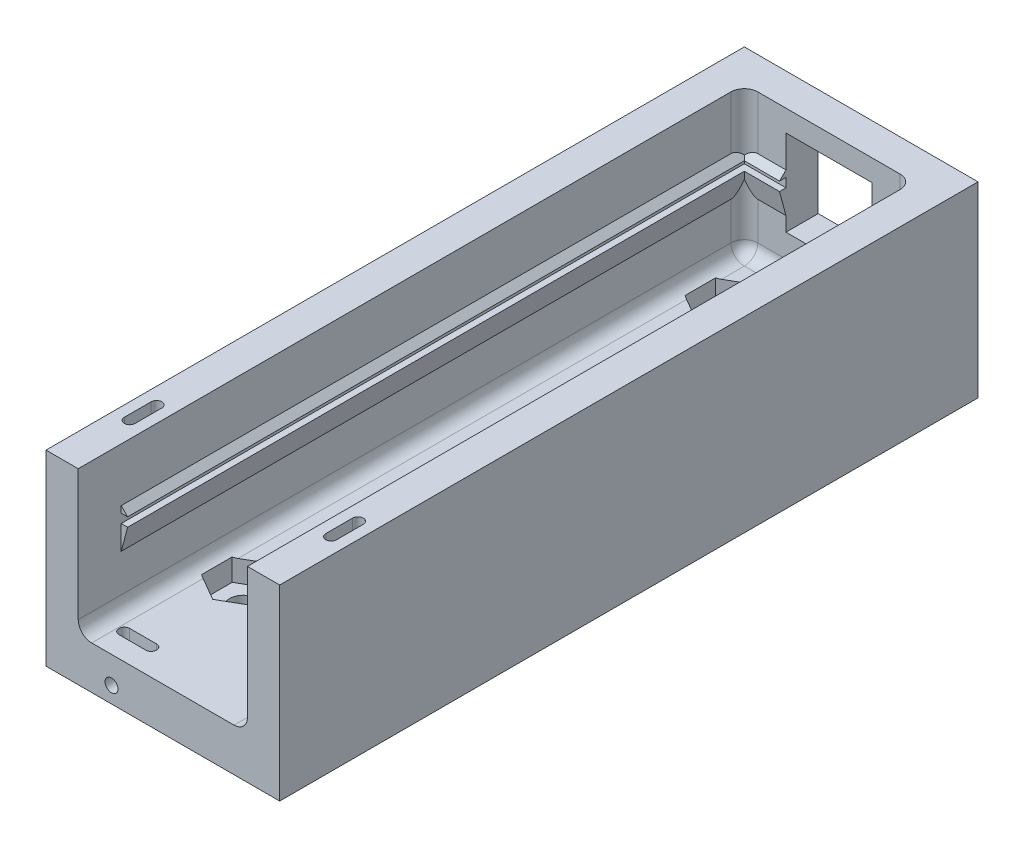
SolidWorks part; units mm, degrees
ref_plane "Front Plane" through (0, 0, 0) normal (0, 0, 1) x (1, 0, 0)
ref_plane "Top Plane" through (0, 0, 0) normal (0, 1, 0) x (1, 0, 0)
ref_plane "Right Plane" through (0, 0, 0) normal (1, 0, 0) x (0, 0, -1)
sketch "Sketch1" plane through (0, 0, 0) normal (0, 0, 1) x (1, 0, 0)
  line L0 (0, 8.7277) -> (0, -3.7047) construction
  line L2 (10.0012, 12.065) -> (10.0012, -8.255)
  line L3 (10.0012, -8.255) -> (-10.0012, -8.255)
  line L4 (-10.0012, 12.065) -> (-10.0012, -8.255)
  line L7 (13.8113, 12.065) -> (10.0012, 12.065)
  line L8 (13.8113, 12.065) -> (13.8113, -13.335)
  line L9 (13.8113, -13.335) -> (-13.8112, -13.335)
  line L10 (-13.8112, 12.065) -> (-13.8112, -13.335)
  line L14 (-10.0012, 12.065) -> (-13.8112, 12.065)
  dimension "D1" = 20.0025
  dimension "D2" = 20.32
  dimension "D3" = 3.81
  dimension "D4" = 3.81
  dimension "D5" = 5.08
  dimension "D6" = 8.255
extrude "Boss-Extrude1" add sketch "Sketch1" along normal blind 82.55
sketch "Sketch3" plane through (0, 0, 82.55) normal (0, 0, 1) x (1, 0, 0)
  line L0 (10.0012, 12.065) -> (10.0012, -8.255) construction
  line L1 (10.0012, 1.7018) -> (9.2392, 1.7018)
  line L2 (10.0012, -8.255) -> (-10.0012, -8.255) construction
  line L3 (10.0012, 0.635) -> (9.2392, 0.635)
  line L4 (-10.0012, 2.4638) -> (-10.0012, 1.7018)
  line L5 (9.2392, 0.635) -> (10.0012, -2.2088)
  line L6 (10.0012, -2.2088) -> (10.0012, 0.635)
  line L7 (9.2392, 1.7018) -> (10.0012, 2.4638)
  line L8 (10.0012, 2.4638) -> (10.0012, 1.7018)
  line L9 (0, 5.2449) -> (0, -5.0535) construction
  line L10 (-9.2392, 1.7018) -> (-10.0012, 2.4638)
  line L11 (-10.0012, -2.2088) -> (-10.0012, 0.635)
  line L12 (-9.2392, 0.635) -> (-10.0012, -2.2088)
  line L13 (-10.0012, 0.635) -> (-9.2392, 0.635)
  line L14 (-10.0012, 1.7018) -> (-9.2392, 1.7018)
  dimension "D1" = 1.0668
  dimension "D2" = 0.762
  dimension "D3" = 0.762
  dimension "D4" = 45
  dimension "D5" = 75
  dimension "D6" = 8.89
extrude "Boss-Extrude2" add sketch "Sketch3" against normal up to surface (77.47 mm away) from offset 5.08 up to face at (0, 0.635, 0) offset against normal yes
sketch "Sketch8" plane through (0, 12.065, 0) normal (0, 1, 0) x (1, 0, 0)
  line L0 (13.8113, -82.55) -> (13.8113, 0) construction
  line L1 (-13.8112, 0) -> (13.8113, 0)
  line L2 (-13.8112, 0) -> (-13.8112, -3.81)
  line L3 (-13.8112, -3.81) -> (13.8113, -3.81)
  line L4 (13.8113, 0) -> (13.8113, -3.81)
  dimension "D1" = 3.81
extrude "Boss-Extrude4" add sketch "Sketch8" against normal up to surface (20.32 mm away) up to face at (0, -8.255, 41.275)
sketch "Sketch9" plane through (-10.0012, 0, 0) normal (1, 0, 0) x (0, 0, -1)
  line L6 (-3.81, 2.4638) -> (-3.81, 1.7018)
  line L7 (-3.81, 1.7018) -> (-4.572, 1.7018)
  line L8 (-3.81, 1.7018) -> (-77.47, 1.7018) construction
  line L9 (-4.572, 1.7018) -> (-3.81, 2.4638)
  line L10 (-3.81, 0.635) -> (-3.81, -2.2088)
  line L11 (-3.81, -2.2088) -> (-4.572, 0.635)
  line L12 (-3.81, 0.635) -> (-77.47, 0.635) construction
  line L13 (-4.572, 0.635) -> (-3.81, 0.635)
  dimension "D4" = 45
  dimension "D5" = 15
extrude "Boss-Extrude5" add sketch "Sketch9" along normal up to surface (20.0025 mm away) up to face at (10.0012, 1.067, 41.4867)
sketch "Sketch10" plane through (0, 0, 0) normal (0, 0, -1) x (-1, 0, 0)
  line L0 (0, 3.2514) -> (0, -1.5042) construction
  line L1 (5.08, -3.9116) -> (-5.08, -3.9116)
  line L2 (5.08, -3.9116) -> (5.08, 6.2484)
  line L3 (5.08, 6.2484) -> (-5.08, 6.2484)
  line L4 (-5.08, -3.9116) -> (-5.08, 6.2484)
  line L7 (2.0868, 1.1684) -> (-3.2166, 1.1684) construction
  line L10 (-9.2392, 1.7018) -> (9.2392, 1.7018) construction
  dimension "D1" = 10.16
  dimension "D2" = 10.16
  dimension "D3" = 0.5334
extrude "Cut-Extrude1" cut sketch "Sketch10" against normal up to next
sketch "Sketch11" plane through (0, 0, 82.55) normal (0, 0, 1) x (1, 0, 0)
  line L0 (13.8113, -13.335) -> (13.8113, 12.065) construction
  line L1 (-13.8112, 12.065) -> (13.8113, 12.065)
  line L2 (-13.8112, 12.065) -> (-13.8112, 8.7884)
  line L3 (-13.8112, 8.7884) -> (13.8113, 8.7884)
  line L4 (13.8113, 12.065) -> (13.8113, 8.7884)
  line L5 (-5.08, 6.2484) -> (5.08, 6.2484) construction
  dimension "D1" = 2.54
extrude "Cut-Extrude2" cut sketch "Sketch11" against normal through all
fillet "Fillet3" radius 1.5875 7 edges at (-10.0012, 5.6261, 3.81) (10.0012, 5.6261, 3.81) (10.0012, -5.2319, 3.81) (-10.0012, -5.2319, 3.81) (10.0012, -8.255, 43.18) (0, -8.255, 3.81) (-10.0012, -8.255, 43.18)
sketch "Sketch13" plane through (0, -8.255, 0) normal (0, 1, 0) x (1, 0, 0)
  line L0 (-7.6519, -79.4512) -> (-4.4769, -79.4512) construction
  line L1 (-7.6519, -78.8162) -> (-4.4769, -78.8162)
  line L2 (-7.6519, -80.0862) -> (-4.4769, -80.0862)
  line L3 (-8.4137, -3.81) -> (8.4137, -3.81) construction
  arc A0 (-7.6519, -78.8162) -> (-7.6519, -80.0862) centre (-7.6519, -79.4512) ccw
  arc A1 (-4.4769, -80.0862) -> (-4.4769, -78.8162) centre (-4.4769, -79.4512) ccw
  point P2 (-6.0644, -79.4512)
  dimension "D3" = 0.635
  dimension "D1" = 75.0062
  dimension "D2" = 3.175
extrude "Cut-Extrude3" cut sketch "Sketch13" against normal blind 2.286
sketch "Sketch14" plane through (0, 8.7884, 0) normal (0, 1, 0) x (1, 0, 0)
  line L0 (-11.9062, -71.387) -> (-11.9062, -74.562) construction
  line L1 (-11.2712, -71.387) -> (-11.2712, -74.562)
  line L2 (-12.5412, -71.387) -> (-12.5412, -74.562)
  line L3 (-10.0012, -5.3975) -> (-10.0012, -82.55) construction
  line L4 (-13.8112, 0) -> (-13.8112, -82.55) construction
  line L5 (-4.4769, -78.8162) -> (-7.6519, -78.8162) construction
  line L6 (0, -43.2809) -> (0, -94.1632) construction
  line L7 (11.9062, -71.387) -> (11.9062, -74.562) construction
  line L8 (11.2712, -71.387) -> (11.2712, -74.562)
  line L9 (12.5412, -71.387) -> (12.5412, -74.562)
  arc A0 (-11.2712, -71.387) -> (-12.5412, -71.387) centre (-11.9062, -71.387) ccw
  arc A1 (-12.5412, -74.562) -> (-11.2712, -74.562) centre (-11.9062, -74.562) ccw
  arc A2 (11.2712, -71.387) -> (12.5412, -71.387) centre (11.9062, -71.387) cw
  arc A3 (12.5412, -74.562) -> (11.2712, -74.562) centre (11.9062, -74.562) cw
  point P2 (-11.9062, -72.9745)
  point P18 (11.9062, -72.9745)
  dimension "D1" = 0.635
  dimension "D2" = 4.2542
  dimension "D3" = 3.175
extrude "Cut-Extrude4" cut sketch "Sketch14" against normal blind 3.175
hole_wizard "#4 Clearance Hole1" positions "Sketch16" profile "Sketch15" hole size "#4" standard "ANSI Inch" end condition up to next
sketch "Sketch16" plane through (0, -8.255, 0) normal (0, 1, 0) x (1, 0, 0)
  line L0 (0, -7.3362) -> (0, -55.1556) construction
  line L2 (8.4137, -82.55) -> (-8.4137, -82.55) construction
  point P0 (-5.715, -10.16)
  point P2 (5.715, -67.31)
  point P4 (-5.715, -67.31)
  point P6 (5.715, -10.16)
  dimension "D1" = 57.15
  dimension "D2" = 11.43
  dimension "D3" = 15.24
sketch "Sketch15" plane through (-5.715, -8.255, 10.16) normal (1, 0, 0) x (0, 0, 1)
  line L0 (0, 0) -> (0, 5.08)
  line L1 (0, 5.08) -> (1.6319, 5.08)
  line L2 (1.6319, 5.08) -> (1.6319, 0)
  line L5 (1.6319, 0) -> (0, 0)
  line L11 (0, -6.35) -> (0, 107.95) construction
  dimension "Thru Hole Dia." = 3.2639
  dimension "Thru Hole Depth" = 5.08
sketch "Sketch17" plane through (0, -8.255, 0) normal (0, 1, 0) x (1, 0, 0)
  line L1 (-5.715, -13.7822) -> (-2.5781, -11.9711)
  line L2 (-2.5781, -11.9711) -> (-2.5781, -8.3489)
  line L3 (-2.5781, -8.3489) -> (-5.715, -6.5378)
  line L4 (-5.715, -6.5378) -> (-8.8519, -8.3489)
  line L5 (-8.8519, -8.3489) -> (-8.8519, -11.9711)
  line L6 (-8.8519, -11.9711) -> (-5.715, -13.7822)
  line L7 (5.715, -13.7822) -> (8.8519, -11.9711)
  line L8 (8.8519, -11.9711) -> (8.8519, -8.3489)
  line L9 (8.8519, -8.3489) -> (5.715, -6.5378)
  line L10 (5.715, -6.5378) -> (2.5781, -8.3489)
  line L11 (2.5781, -8.3489) -> (2.5781, -11.9711)
  line L12 (2.5781, -11.9711) -> (5.715, -13.7822)
  line L13 (-5.715, -63.6878) -> (-8.8519, -65.4989)
  line L14 (-8.8519, -65.4989) -> (-8.8519, -69.1211)
  line L15 (-8.8519, -69.1211) -> (-5.715, -70.9322)
  line L16 (-5.715, -70.9322) -> (-2.5781, -69.1211)
  line L17 (-2.5781, -69.1211) -> (-2.5781, -65.4989)
  line L18 (-2.5781, -65.4989) -> (-5.715, -63.6878)
  line L19 (5.715, -63.6878) -> (2.5781, -65.4989)
  line L20 (2.5781, -65.4989) -> (2.5781, -69.1211)
  line L21 (2.5781, -69.1211) -> (5.715, -70.9322)
  line L22 (5.715, -70.9322) -> (8.8519, -69.1211)
  line L23 (8.8519, -69.1211) -> (8.8519, -65.4989)
  line L24 (8.8519, -65.4989) -> (5.715, -63.6878)
  circle A0 centre (-5.715, -10.16) radius 3.1369 construction
  circle A1 centre (5.715, -10.16) radius 3.1369 construction
  circle A2 centre (-5.715, -67.31) radius 3.1369 construction
  circle A3 centre (5.715, -67.31) radius 3.1369 construction
  dimension "D2" = 6.2738
extrude "Cut-Extrude5" cut sketch "Sketch17" against normal blind 2.54 and the other way up to next
sketch "Sketch18" plane through (0, 0, 82.55) normal (0, 0, 1) x (1, 0, 0)
  circle A0 centre (-6.0645, -11.43) radius 0.762
  dimension "D1" = 1.524
extrude "Cut-Extrude6" cut sketch "Sketch18" against normal blind 10.16
